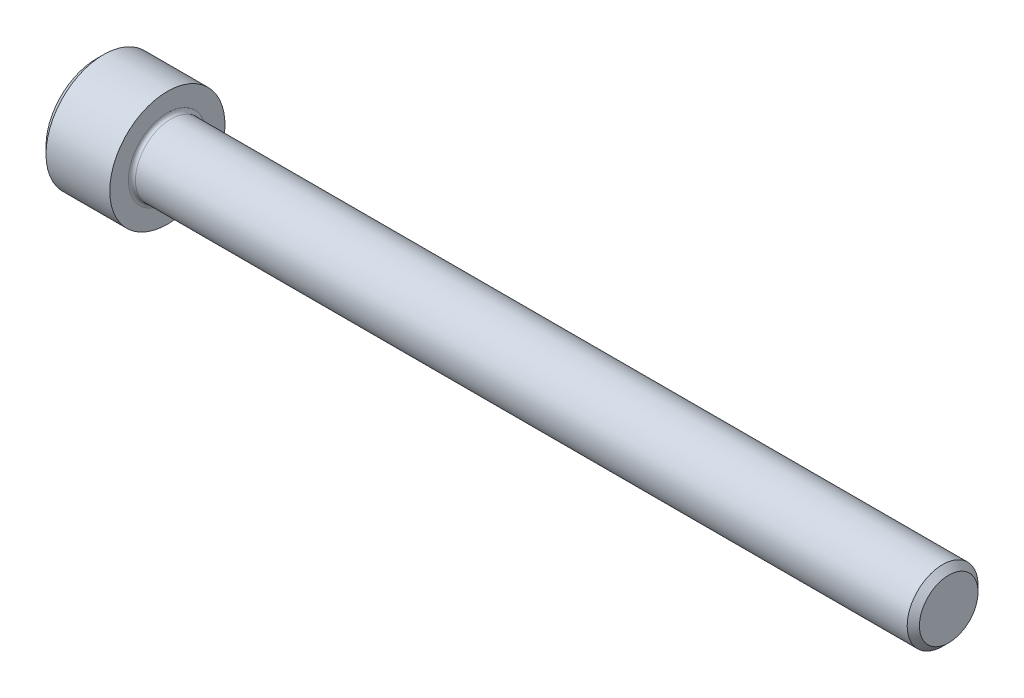
SolidWorks part; units mm, degrees
revolve "Base-Revolve" add sketch "BodySke"
sketch "BodySke" plane through (0, 0, 0) normal (0, 0, 1) x (1, 0, 0)
  line L0 (0, 0) -> (0, 5.7)
  line L1 (0.8, 6.5) -> (8, 6.5)
  line L2 (8, 6.5) -> (8, 4)
  line L3 (8, 4) -> (95.5095, 4)
  line L5 (96.2, 0) -> (0, 0)
  line L6 (-31.75, 0) -> (127, 0) construction
  line L7 (0, 5.7) -> (0.8, 6.5)
  line L9 (0, -5.7) -> (0.8, -6.5) construction
  line L10 (20, -3.3095) -> (19.3095, -4) construction
  line L11 (9.25, 9.525) -> (9.25, 3.175) construction
  line L12 (8, 9.525) -> (8, 3.175) construction
  line L13 (-30, 9.525) -> (-30, 3.175) construction
  line L14 (96.2, 3.3095) -> (96.2, 0)
  line L15 (96.2, 3.3095) -> (95.5095, 4)
  dimension "Diameter" = 8
  dimension "Head_ht" = 8
  dimension "Head_dia" = 13
  dimension "Head_ch_ang" = 45
  dimension "Advance" = 1.25
  dimension "Head_ch_ht" = 0.8
cosmetic thread "ThreadCosmetic" [suppressed]
fillet "Fillet1" radius 0.4 1 edges at (8, 0, 4)
ref_plane "Plane1" through (0, 0, 0) normal (0, 0, 1) x (1, 0, 0)
ref_plane "Plane2" through (0, 0, 0) normal (0, 1, 0) x (1, 0, 0)
ref_plane "Plane3" through (0, 0, 0) normal (1, 0, 0) x (0, 0, -1)
sketch "Sketch2" plane through (0, 0, 0) normal (0, 0, 1) x (1, 0, 0)
  line L0 (0, 3.0475) -> (4, 3.0475)
  line L1 (4, 3.0475) -> (5.7595, 0)
  line L2 (-31.75, 0) -> (127, 0) construction
  line L3 (5.7595, 0) -> (0, 0)
  line L4 (0, 0) -> (0, 3.0475)
  line L5 (0, 5.7) -> (0, -5.7) construction
  line L6 (0, 0) -> (47.625, 0) construction
  line L7 (8, -6.5) -> (8, 6.5) construction
  dimension "D1" = 3.0475
  dimension "D2" = 60
revolve "Hex-PreBroach" cut sketch "Sketch2" angle 360 about L6
sketch "Sketch3" plane through (0, 0, 0) normal (-1, 0, 0) x (0, 0.5, 0.866)
  line L0 (1.7595, 3.0475) -> (-1.7595, 3.0475)
  line L1 (-1.7595, 3.0475) -> (-3.5189, 0)
  line L2 (1.7595, 3.0475) -> (3.5189, 0)
  line L3 (1.7595, -3.0475) -> (3.5189, 0)
  line L4 (1.7595, -3.0475) -> (-1.7595, -3.0475)
  line L5 (-1.7595, -3.0475) -> (-3.5189, 0)
  dimension "D1" = 3.0475
  dimension "D2" = 3.0475
  dimension "Hex_size" = 6.095
extrude "Hex" cut sketch "Sketch3" against normal blind 4
sketch "Sketch4" plane through (0, 0, 0) normal (-1, 0, 0) x (0, 0, 1)
  line L0 (0, 0) -> (3.7846, 0)
  line L1 (0, 0) -> (6.1484, 3.5498) construction
  line L2 (0, 0) -> (1.8923, 3.2776)
  line L3 (3.1235, 0.8061) -> (3.6229, 1.0945)
  line L4 (2.2599, 2.3019) -> (2.7593, 2.5903)
  arc A0 (3.1235, 0.8061) -> (2.2599, 2.3019) centre (0, 0) ccw
  arc A1 (3.7846, 0) -> (3.6229, 1.0945) centre (0, 0) ccw
  arc A2 (1.8923, 3.2776) -> (2.7593, 2.5903) centre (0, 0) cw
  dimension "D1" = 30
  dimension "D2" = 60
  dimension "Spline_p_dim" = 1.7272
  dimension "D3" = 0.8636
extrude "Spline" [suppressed] cut sketch "Sketch4" against normal blind 4
pattern_circular "CirPattern1" [suppressed] count 6 every 60
sketch "Sketch5" plane through (0, 0, 0) normal (0, 0, 1) x (1, 0, 0)
  line L0 (-31.75, 0) -> (127, 0) construction
  line L2 (0, 5.7) -> (0, -5.7) construction
  circle A0 centre (2.7, 0) radius 0.675
  dimension "Drilled_hole_dia" = 1.35
  dimension "Drilled_hole_loc" = 2.7
extrude "Hole" [suppressed] cut sketch "Sketch5" against normal through all and the other way through all
pattern_circular "Drilled-4" [suppressed] count 2 every 60
pattern_circular "Drilled-6" [suppressed] count 3 every 60
sketch "ThdSchSke" plane through (0, 0, 0) normal (0, 0, 1) x (1, 0, 0)
  line L0 (9.25, -3.3095) -> (8.7665, -4)
  line L1 (9.25, -3.3095) -> (9.7335, -4)
  line L2 (9.7335, -4) -> (9.7335, -5)
  line L3 (-3.175, 0) -> (5.1513, 0) construction
  line L5 (9.7335, -5) -> (8.7665, -5)
  line L6 (8.7665, -5) -> (8.7665, -4)
  line L7 (0, 5.7) -> (0, -5.7) construction
  dimension "Thread_minor" = 6.619
  dimension "Diameter" = 8
  dimension "Start" = 9.25
revolve "ThreadSchematic" [suppressed] cut sketch "ThdSchSke" angle 360 about L3
pattern_linear "ThdSchPat" [suppressed]
equation "\"D2@Sketch3\" = \"Hex_size@Sketch3\" / 2"
equation "\"D1@Sketch3\" = \"Hex_size@Sketch3\" / 2"
equation "\"D1@Sketch2\" = \"Hex_size@Sketch3\" / 2"
equation "\"D3@Sketch4\" = \"Spline_p_dim@Sketch4\" / 2"
equation "\"D2@CirPattern1\" = 360 / \"Num_teeth@CirPattern1\""
equation "\"Wall_thickness@Sketch2\" = \"Head_ht@BodySke\" - \"Key_eng@Hex\""
equation "\"Diameter@ThdSchSke\" = \"Diameter@BodySke\""
equation "\"Overcut@ThdSchSke\" = \"Diameter@BodySke\" * 1.25"
equation "\"Num_threads@ThdSchPat\" = int( \"Thread_length@ThreadCosmetic\" / \"Advance@BodySke\" + 0.999 )  + 1"
equation "\"Advance@ThdSchPat\" = \"Thread_length@ThreadCosmetic\" /  (\"Num_threads@ThdSchPat\" - 1) 'relax it"
equation "\"Num_threads@ThdSchPat\" = \"Num_threads@ThdSchPat\" - sgn( \"Num_threads@ThdSchPat\" - 1) '---chamfered tips only---"
